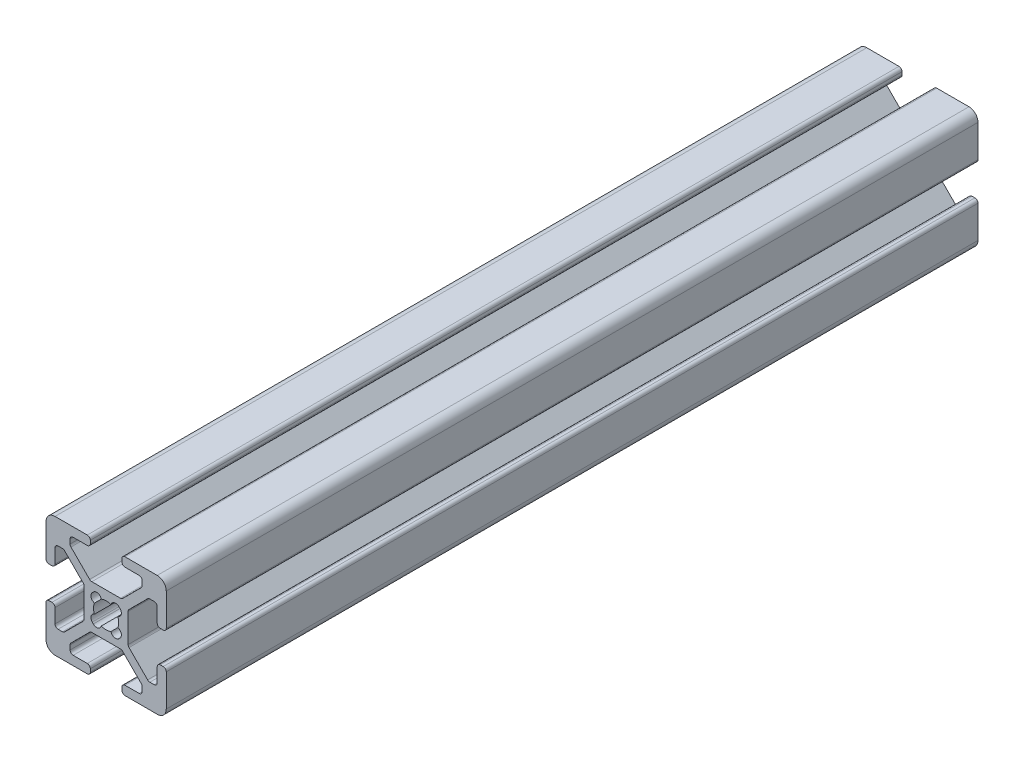
SolidWorks part; units mm, degrees
ref_plane "Front Plane" through (0, 0, 0) normal (0, 0, 1) x (1, 0, 0)
ref_plane "Top Plane" through (0, 0, 0) normal (0, 1, 0) x (1, 0, 0)
ref_plane "Right Plane" through (0, 0, 0) normal (1, 0, 0) x (0, 0, -1)
sketch "Sketch1" plane through (0, 0, 0) normal (0, 0, 1) x (1, 0, 0)
  line L0 (-5.0323, -0.3411) -> (-5.5163, -0.3411)
  line L1 (-6.0243, 0.1669) -> (-6.0243, 2.5159)
  line L2 (-4.5243, 0.1669) -> (-4.5243, 5.5289)
  line L3 (-10.8693, -5.355) -> (-10.8693, -0.5871)
  line L4 (-7.2582, 3.0239) -> (-6.5323, 3.0239)
  line L5 (-7.6174, 2.8752) -> (-10.7205, -0.2279)
  line L6 (-5.0323, -5.6011) -> (-5.5163, -5.6011)
  line L7 (-4.5243, -6.1091) -> (-4.5243, -11.4711)
  line L8 (-6.0243, -6.1091) -> (-6.0243, -8.4581)
  line L9 (-7.2582, -8.9661) -> (-6.5323, -8.9661)
  line L10 (-7.6174, -8.8173) -> (-10.7205, -5.7142)
  line L11 (-12.3994, -5.2756) -> (-12.2198, -5.096)
  line L12 (-17.1543, 6.5209) -> (-17.1543, 6.0369)
  line L13 (-17.6623, 7.0289) -> (-23.0243, 7.0289)
  line L14 (-17.6623, 5.5289) -> (-20.0113, 5.5289)
  line L15 (-12.1404, 0.6839) -> (-16.9082, 0.6839)
  line L16 (-20.5193, 4.295) -> (-20.5193, 5.0209)
  line L17 (-20.3705, 3.9358) -> (-17.2674, 0.8327)
  line L18 (-11.8943, 6.5209) -> (-11.8943, 6.0369)
  line L19 (-11.3863, 7.0289) -> (-6.0243, 7.0289)
  line L20 (-11.3863, 5.5289) -> (-9.0373, 5.5289)
  line L21 (-8.5293, 4.295) -> (-8.5293, 5.0209)
  line L22 (-8.6781, 3.9358) -> (-11.7812, 0.8327)
  line L23 (-12.2198, -0.8462) -> (-12.3994, -0.6666)
  line L24 (-24.0163, -5.6011) -> (-23.5323, -5.6011)
  line L25 (-24.5243, -6.1091) -> (-24.5243, -11.4711)
  line L26 (-23.0243, -6.1091) -> (-23.0243, -8.4581)
  line L27 (-18.1793, -0.5871) -> (-18.1793, -5.355)
  line L28 (-21.7904, -8.9661) -> (-22.5163, -8.9661)
  line L29 (-21.4312, -8.8173) -> (-18.3281, -5.7142)
  line L30 (-24.0163, -0.3411) -> (-23.5323, -0.3411)
  line L31 (-24.5243, 0.1669) -> (-24.5243, 5.5289)
  line L32 (-23.0243, 0.1669) -> (-23.0243, 2.5159)
  line L33 (-21.7904, 3.0239) -> (-22.5163, 3.0239)
  line L34 (-21.4312, 2.8752) -> (-18.3281, -0.2279)
  line L35 (-16.6492, -0.6666) -> (-16.8288, -0.8462)
  line L36 (-11.8943, -12.4631) -> (-11.8943, -11.9791)
  line L37 (-11.3863, -12.9711) -> (-6.0243, -12.9711)
  line L38 (-11.3863, -11.4711) -> (-9.0373, -11.4711)
  line L39 (-16.9082, -6.6261) -> (-12.1404, -6.6261)
  line L40 (-8.5293, -10.2371) -> (-8.5293, -10.9631)
  line L41 (-8.6781, -9.8779) -> (-11.7812, -6.7748)
  line L42 (-17.1543, -12.4631) -> (-17.1543, -11.9791)
  line L43 (-17.6623, -12.9711) -> (-23.0243, -12.9711)
  line L44 (-17.6623, -11.4711) -> (-20.0113, -11.4711)
  line L45 (-20.5193, -10.2371) -> (-20.5193, -10.9631)
  line L46 (-20.3705, -9.8779) -> (-17.2674, -6.7748)
  line L47 (-16.8288, -5.096) -> (-16.6492, -5.2756)
  arc A0 (-15.3283, -4.9062) -> (-13.7203, -4.9062) centre (-14.5243, -2.9711) ccw
  arc A1 (-6.0243, 2.5159) -> (-6.5323, 3.0239) centre (-6.5323, 2.5159) ccw
  arc A2 (-7.2582, 3.0239) -> (-7.6174, 2.8752) centre (-7.2582, 2.5159) ccw
  arc A3 (-10.7205, -0.2279) -> (-10.8693, -0.5871) centre (-10.3613, -0.5871) ccw
  arc A4 (-10.8693, -5.355) -> (-10.7205, -5.7142) centre (-10.3613, -5.355) ccw
  arc A5 (-7.6174, -8.8173) -> (-7.2582, -8.9661) centre (-7.2582, -8.4581) ccw
  arc A6 (-6.5323, -8.9661) -> (-6.0243, -8.4581) centre (-6.5323, -8.4581) ccw
  arc A7 (-5.5163, -5.6011) -> (-6.0243, -6.1091) centre (-5.5163, -6.1091) ccw
  arc A8 (-4.5243, -6.1091) -> (-5.0323, -5.6011) centre (-5.0323, -6.1091) ccw
  arc A9 (-5.0323, -0.3411) -> (-4.5243, 0.1669) centre (-5.0323, 0.1669) ccw
  arc A10 (-6.0243, 0.1669) -> (-5.5163, -0.3411) centre (-5.5163, 0.1669) ccw
  arc A11 (-13.7203, -4.9062) -> (-12.3994, -5.2756) centre (-12.9559, -4.7191) ccw
  arc A12 (-12.2198, -5.096) -> (-12.5892, -3.775) centre (-12.7763, -4.5395) ccw
  arc A13 (-17.1543, 6.5209) -> (-17.6623, 7.0289) centre (-17.6623, 6.5209) ccw
  arc A14 (-17.6623, 5.5289) -> (-17.1543, 6.0369) centre (-17.6623, 6.0369) ccw
  arc A15 (-12.5892, -3.775) -> (-12.5892, -2.1671) centre (-14.5243, -2.9711) ccw
  arc A16 (-17.2674, 0.8327) -> (-16.9082, 0.6839) centre (-16.9082, 1.1919) ccw
  arc A17 (-20.0113, 5.5289) -> (-20.5193, 5.0209) centre (-20.0113, 5.0209) ccw
  arc A18 (-20.5193, 4.295) -> (-20.3705, 3.9358) centre (-20.0113, 4.295) ccw
  arc A19 (-11.8943, 6.0369) -> (-11.3863, 5.5289) centre (-11.3863, 6.0369) ccw
  arc A20 (-11.3863, 7.0289) -> (-11.8943, 6.5209) centre (-11.3863, 6.5209) ccw
  arc A21 (-8.5293, 5.0209) -> (-9.0373, 5.5289) centre (-9.0373, 5.0209) ccw
  arc A22 (-8.6781, 3.9358) -> (-8.5293, 4.295) centre (-9.0373, 4.295) ccw
  arc A23 (-12.1404, 0.6839) -> (-11.7812, 0.8327) centre (-12.1404, 1.1919) ccw
  arc A24 (-12.5892, -2.1671) -> (-12.2198, -0.8462) centre (-12.7763, -1.4027) ccw
  arc A25 (-12.3994, -0.6666) -> (-13.7203, -1.0359) centre (-12.9559, -1.223) ccw
  arc A26 (-24.0163, -5.6011) -> (-24.5243, -6.1091) centre (-24.0163, -6.1091) ccw
  arc A27 (-23.0243, -6.1091) -> (-23.5323, -5.6011) centre (-23.5323, -6.1091) ccw
  arc A28 (-13.7203, -1.0359) -> (-15.3283, -1.0359) centre (-14.5243, -2.9711) ccw
  arc A29 (-18.3281, -5.7142) -> (-18.1793, -5.355) centre (-18.6873, -5.355) ccw
  arc A30 (-23.0243, -8.4581) -> (-22.5163, -8.9661) centre (-22.5163, -8.4581) ccw
  arc A31 (-21.7904, -8.9661) -> (-21.4312, -8.8173) centre (-21.7904, -8.4581) ccw
  arc A32 (-23.5323, -0.3411) -> (-23.0243, 0.1669) centre (-23.5323, 0.1669) ccw
  arc A33 (-24.5243, 0.1669) -> (-24.0163, -0.3411) centre (-24.0163, 0.1669) ccw
  arc A34 (-22.5163, 3.0239) -> (-23.0243, 2.5159) centre (-22.5163, 2.5159) ccw
  arc A35 (-21.4312, 2.8752) -> (-21.7904, 3.0239) centre (-21.7904, 2.5159) ccw
  arc A36 (-18.1793, -0.5871) -> (-18.3281, -0.2279) centre (-18.6873, -0.5871) ccw
  arc A37 (-15.3283, -1.0359) -> (-16.6492, -0.6666) centre (-16.0927, -1.223) ccw
  arc A38 (-16.8288, -0.8462) -> (-16.4594, -2.1671) centre (-16.2723, -1.4027) ccw
  arc A39 (-11.8943, -12.4631) -> (-11.3863, -12.9711) centre (-11.3863, -12.4631) ccw
  arc A40 (-11.3863, -11.4711) -> (-11.8943, -11.9791) centre (-11.3863, -11.9791) ccw
  arc A41 (-16.4594, -2.1671) -> (-16.4594, -3.775) centre (-14.5243, -2.9711) ccw
  arc A42 (-11.7812, -6.7748) -> (-12.1404, -6.6261) centre (-12.1404, -7.1341) ccw
  arc A43 (-9.0373, -11.4711) -> (-8.5293, -10.9631) centre (-9.0373, -10.9631) ccw
  arc A44 (-8.5293, -10.2371) -> (-8.6781, -9.8779) centre (-9.0373, -10.2371) ccw
  arc A45 (-17.1543, -11.9791) -> (-17.6623, -11.4711) centre (-17.6623, -11.9791) ccw
  arc A46 (-17.6623, -12.9711) -> (-17.1543, -12.4631) centre (-17.6623, -12.4631) ccw
  arc A47 (-20.5193, -10.9631) -> (-20.0113, -11.4711) centre (-20.0113, -10.9631) ccw
  arc A48 (-20.3705, -9.8779) -> (-20.5193, -10.2371) centre (-20.0113, -10.2371) ccw
  arc A49 (-16.9082, -6.6261) -> (-17.2674, -6.7748) centre (-16.9082, -7.1341) ccw
  arc A50 (-16.4594, -3.775) -> (-16.8288, -5.096) centre (-16.2723, -4.5395) ccw
  arc A51 (-16.6492, -5.2756) -> (-15.3283, -4.9062) centre (-16.0927, -4.7191) ccw
  arc A52 (-4.5243, 5.5289) -> (-6.0243, 7.0289) centre (-6.0243, 5.5289) ccw
  arc A53 (-6.0243, -12.9711) -> (-4.5243, -11.4711) centre (-6.0243, -11.4711) ccw
  arc A54 (-24.5243, -11.4711) -> (-23.0243, -12.9711) centre (-23.0243, -11.4711) ccw
  arc A55 (-23.0243, 7.0289) -> (-24.5243, 5.5289) centre (-23.0243, 5.5289) ccw
extrude "Extrude1" add sketch "Sketch1" along normal blind 135
